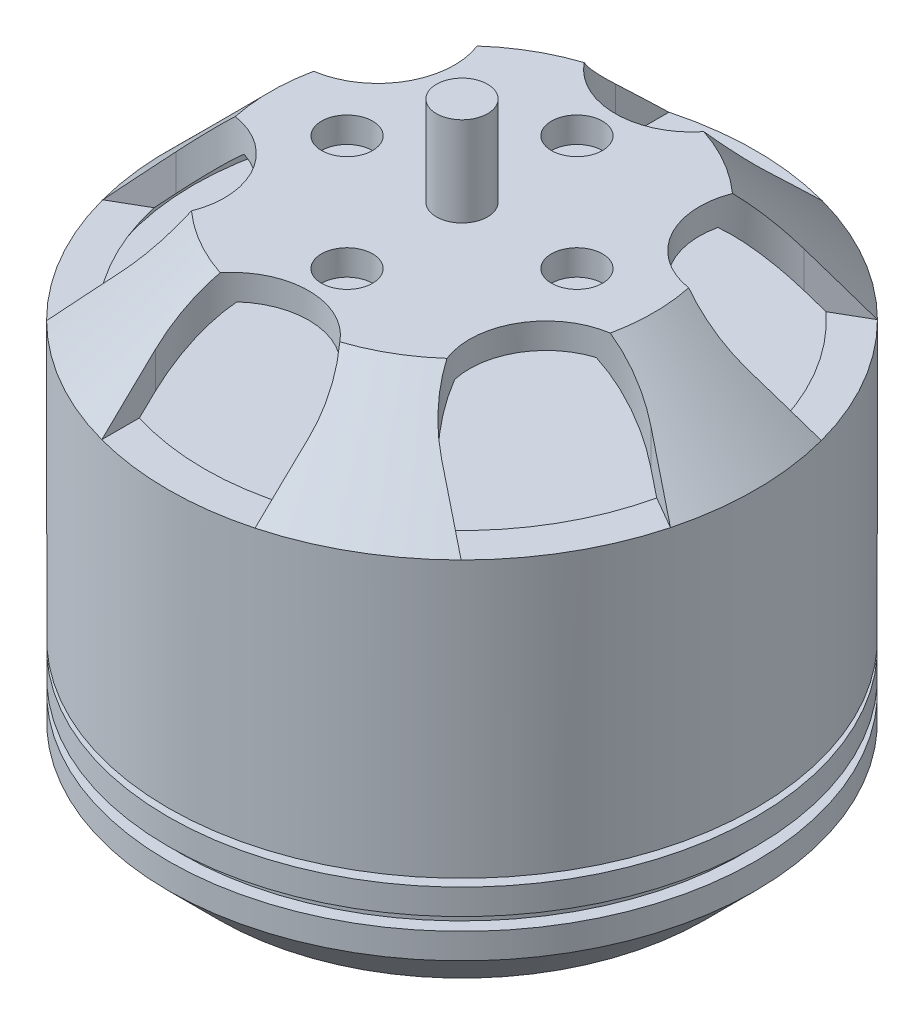
SolidWorks part; units mm, degrees
ref_plane "Front Plane" through (0, 0, 0) normal (0, 0, 1) x (1, 0, 0)
ref_plane "Top Plane" through (0, 0, 0) normal (0, 1, 0) x (1, 0, 0)
ref_plane "Right Plane" through (0, 0, 0) normal (1, 0, 0) x (0, 0, -1)
sketch "Sketch2" plane through (0, 0, 0) normal (0, 0, 1) x (1, 0, 0)
  line L0 (0, 23.8) -> (0, 0)
  line L1 (1, 0.7095) -> (9.5, 0.7095)
  line L2 (9.5, 0.7095) -> (11.5, 2.7095)
  line L3 (11.5, 2.7095) -> (11.5, 3.7095)
  line L4 (11.5, 16.3) -> (7.5, 20.3)
  line L5 (7.5, 20.3) -> (1, 20.3)
  line L6 (1, 20.3) -> (1, 23.8)
  line L7 (1, 23.8) -> (0, 23.8)
  line L8 (0, 0) -> (0, -1.0905)
  line L9 (0, -1.0905) -> (1, -1.0905)
  line L10 (1, -1.0905) -> (1, 0.7095)
  line L11 (2, 19.3) -> (7.0858, 19.3)
  line L12 (7.0858, 19.3) -> (10.5, 15.8858)
  line L13 (10.5, 15.8858) -> (10.5, 15.6412)
  line L14 (10.5, 15.6412) -> (1, 15.6412)
  line L15 (1, 15.6412) -> (1, 18.3)
  line L16 (1, 18.3) -> (2, 18.3)
  line L17 (2, 18.3) -> (2, 19.3)
  line L18 (11.5, 3.7095) -> (11, 3.7095)
  line L19 (11, 3.7095) -> (11, 4.2095)
  line L20 (11, 4.2095) -> (11.5, 4.2095)
  line L21 (11.5, 5.2095) -> (9.5, 5.2095)
  line L22 (9.5, 5.2095) -> (9.5, 5.5095)
  line L23 (9.5, 5.5095) -> (11.5, 5.5095)
  line L24 (11.5, 4.2095) -> (11.5, 5.2095)
  line L25 (11.5, 5.5095) -> (11.5, 16.3)
  dimension "D1" = 23.8
  dimension "D2" = 1.8
  dimension "D3" = 45
  dimension "D4" = 2
  dimension "D5" = 1
  dimension "D6" = 1
  dimension "D7" = 3.5
  dimension "D8" = 11.5
  dimension "D9" = 45
  dimension "D10" = 8.5
  dimension "D11" = 1
  dimension "D12" = 1
  dimension "D13" = 1
  dimension "D14" = 1
  dimension "D15" = 1
  dimension "D16" = 1
  dimension "D17" = 4
  dimension "D18" = 1
  dimension "D19" = 0.5
  dimension "D20" = 0.5
  dimension "D21" = 1
  dimension "D22" = 0.3
  dimension "D23" = 2
revolve "Revolve1" add sketch "Sketch2" angle 360 about L0
sketch "Sketch3" plane through (0, 20.3, 0) normal (0, 1, 0) x (1, 0, 0)
  line L0 (0, 0) -> (0, 9) construction
  line L1 (-3, 9) -> (-3, 17.6722)
  line L2 (-3, 17.6722) -> (3, 17.6722)
  line L3 (3, 17.6722) -> (3, 9)
  line L4 (16.8046, 6.238) -> (9.2942, 1.9019)
  line L5 (6.2942, 7.0981) -> (13.8046, 11.4342)
  line L6 (13.8046, 11.4342) -> (16.8046, 6.238)
  line L7 (13.8046, -11.4342) -> (6.2942, -7.0981)
  line L8 (9.2942, -1.9019) -> (16.8046, -6.238)
  line L9 (16.8046, -6.238) -> (13.8046, -11.4342)
  line L10 (-3, -17.6722) -> (-3, -9)
  line L11 (3, -9) -> (3, -17.6722)
  line L12 (3, -17.6722) -> (-3, -17.6722)
  line L13 (-16.8046, -6.238) -> (-9.2942, -1.9019)
  line L14 (-6.2942, -7.0981) -> (-13.8046, -11.4342)
  line L15 (-13.8046, -11.4342) -> (-16.8046, -6.238)
  line L16 (-13.8046, 11.4342) -> (-6.2942, 7.0981)
  line L17 (-9.2942, 1.9019) -> (-16.8046, 6.238)
  line L18 (-16.8046, 6.238) -> (-13.8046, 11.4342)
  circle A0 centre (0, 0) radius 4.5 construction
  circle A1 centre (0, 0) radius 8.7643 construction
  circle A2 centre (0, -4.5) radius 1
  circle A3 centre (-4.5, 0) radius 1
  circle A4 centre (0, 4.5) radius 1
  circle A5 centre (4.5, 0) radius 1
  arc A6 (-3, 9) -> (3, 9) centre (0, 9) ccw
  arc A7 (6.2942, 7.0981) -> (9.2942, 1.9019) centre (7.7942, 4.5) ccw
  arc A8 (9.2942, -1.9019) -> (6.2942, -7.0981) centre (7.7942, -4.5) ccw
  arc A9 (3, -9) -> (-3, -9) centre (0, -9) ccw
  arc A10 (-6.2942, -7.0981) -> (-9.2942, -1.9019) centre (-7.7942, -4.5) ccw
  arc A11 (-9.2942, 1.9019) -> (-6.2942, 7.0981) centre (-7.7942, 4.5) ccw
  point P16 (0, 0)
  point P45 (0, 0)
  dimension "D1" = 9
  dimension "D3" = 2
  dimension "D5" = 6
  dimension "D2" = 9
  dimension "D4" = 4
  dimension "D6" = 6
extrude "Cut-Extrude1" cut sketch "Sketch3" against normal blind 4
sketch "Sketch4" plane through (0, 0.7095, 0) normal (0, -1, 0) x (1, 0, 0)
  circle A0 centre (0, 0) radius 6 construction
  circle A1 centre (0, 0) radius 8 construction
  circle A2 centre (0, 6) radius 1
  circle A3 centre (8, 0) radius 1
  circle A4 centre (0, -6) radius 1
  circle A5 centre (-8, 0) radius 1
  dimension "D1" = 12
  dimension "D2" = 16
  dimension "D3" = 2
extrude "Cut-Extrude2" cut sketch "Sketch4" against normal blind 3
